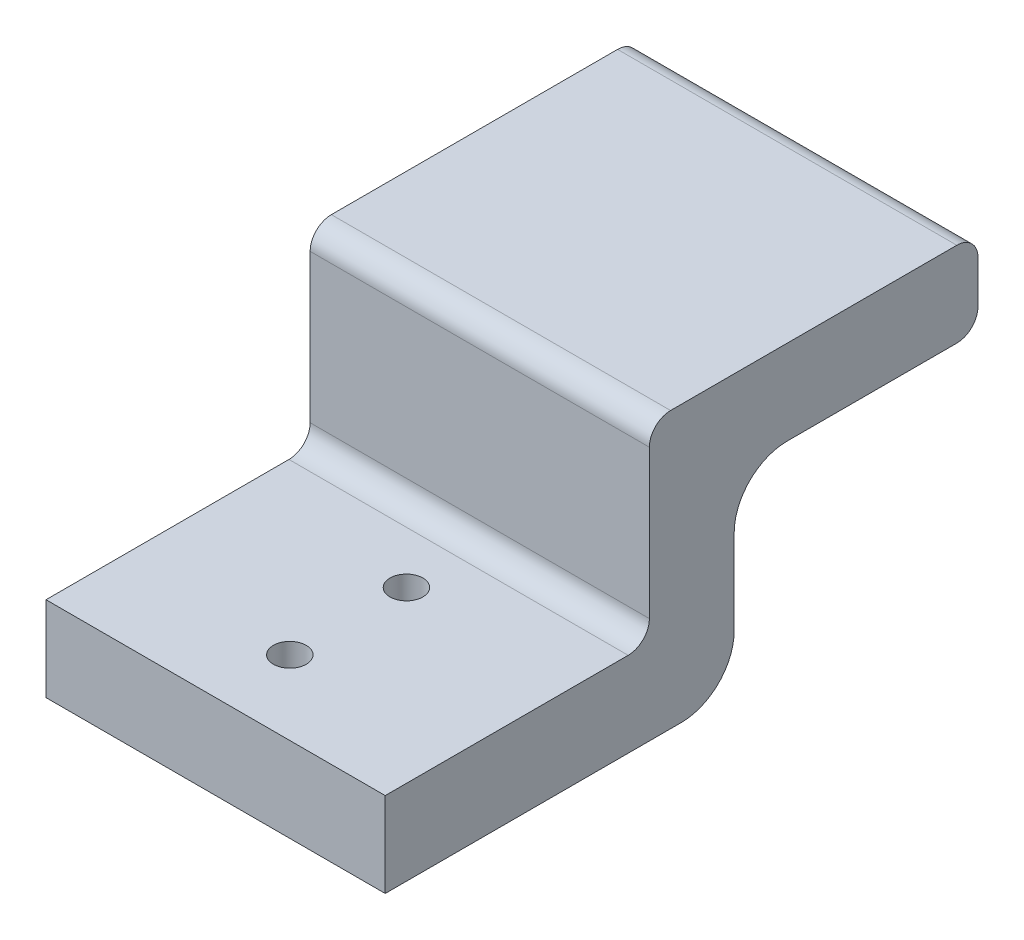
SolidWorks part; units mm, degrees
ref_plane "前视基准面" through (0, 0, 0) normal (0, 0, 1) x (1, 0, 0)
ref_plane "上视基准面" through (0, 0, 0) normal (0, 1, 0) x (1, 0, 0)
ref_plane "右视基准面" through (0, 0, 0) normal (1, 0, 0) x (0, 0, -1)
other "Configuration Table"
ref_plane "基准面1" through (0, 0, 0) normal (0, -1, 0) x (1, 0, 0)
sketch "草图1" plane through (0, 0, 0) normal (0, -1, 0) x (1, 0, 0)
  line L0 (16, -10.4176) -> (16, 22.5)
  line L1 (16, 22.5) -> (-16, 22.5)
  line L2 (-16, 22.5) -> (-16, -10.4176)
  line L8 (-16, -10.4176) -> (16, -10.4176)
extrude "凸台-拉伸1" add sketch "草图1" against normal blind 8
sketch "草图2" plane through (0, 0, 0) normal (0, -1, 0) x (1, 0, 0)
  line L0 (-1.6743, 18.4) -> (-3.3486, 15.5)
  line L1 (-3.3486, 15.5) -> (-1.6743, 12.6)
  line L2 (-1.6743, 12.6) -> (1.6743, 12.6)
  line L3 (1.6743, 12.6) -> (3.3486, 15.5)
  line L4 (3.3486, 15.5) -> (1.6743, 18.4)
  line L5 (1.6743, 18.4) -> (-1.6743, 18.4)
extrude "切除-拉伸1" cut sketch "草图2" against normal blind 2.8
sketch "草图3" plane through (0, 0, 0) normal (0, -1, 0) x (1, 0, 0)
  line L0 (1.6743, 7.4) -> (-1.6743, 7.4)
  line L1 (-1.6743, 7.4) -> (-3.3486, 4.5)
  line L2 (-3.3486, 4.5) -> (-1.6743, 1.6)
  line L3 (-1.6743, 1.6) -> (1.6743, 1.6)
  line L4 (1.6743, 1.6) -> (3.3486, 4.5)
  line L5 (3.3486, 4.5) -> (1.6743, 7.4)
extrude "切除-拉伸2" cut sketch "草图3" against normal blind 2.8
hole_wizard "Ø3.1 (3.1) 直径孔1" positions "草图5" profile "草图4" hole size "Ø3.1" standard "ANSI Metric"
sketch "草图5" plane through (0, 2.8, 0) normal (0, -1, 0) x (-1, 0, 0)
  point P0 (0, -4.5)
  point P1 (0, -15.5)
sketch "草图4" plane through (0, 2.8, 4.5) normal (1, 0, 0) x (0, 0, -1)
  line L0 (0, 0) -> (0, 5.2)
  line L1 (0, 5.2) -> (1.55, 5.2)
  line L2 (1.55, 5.2) -> (1.55, 0)
  line L5 (1.55, 0) -> (0, 0)
  line L11 (0, -6.35) -> (0, 107.95) construction
  dimension "通孔孔直径" = 3.1
  dimension "通孔孔深度" = 5.2
sketch "草图9" plane through (16, 0, 0) normal (1, 0, 0) x (0, 0, -1)
  line L0 (10.4176, 8) -> (2.4176, 8)
  line L1 (10.4176, 8) -> (10.4176, 26)
  line L2 (2.4176, 8) -> (2.4176, 26)
  line L3 (10.4176, 26) -> (2.4176, 26)
  line L4 (10.4176, 8) -> (-22.5, 8) construction
  dimension "D1" = 8
  dimension "D2" = 18
extrude "凸台-拉伸3" add sketch "草图9" against normal blind 32
sketch "草图10" plane through (16, 0, 0) normal (1, 0, 0) x (0, 0, -1)
  line L0 (10.4176, 26) -> (33.4176, 26)
  line L1 (10.4176, 26) -> (10.4176, 18)
  line L2 (33.4176, 26) -> (33.4176, 18)
  line L3 (10.4176, 18) -> (33.4176, 18)
  dimension "D1" = 8
  dimension "D2" = 23
extrude "凸台-拉伸4" add sketch "草图10" against normal blind 32
fillet "圆角1" radius 2 2 edges at (0, 26, -2.4176) (0, 8, -2.4176)
fillet "圆角2" radius 2 2 edges at (0, 26, -33.4176) (0, 18, -33.4176)
fillet "圆角3" radius 5 2 edges at (0, 0, -10.4176) (0, 18, -10.4176)
